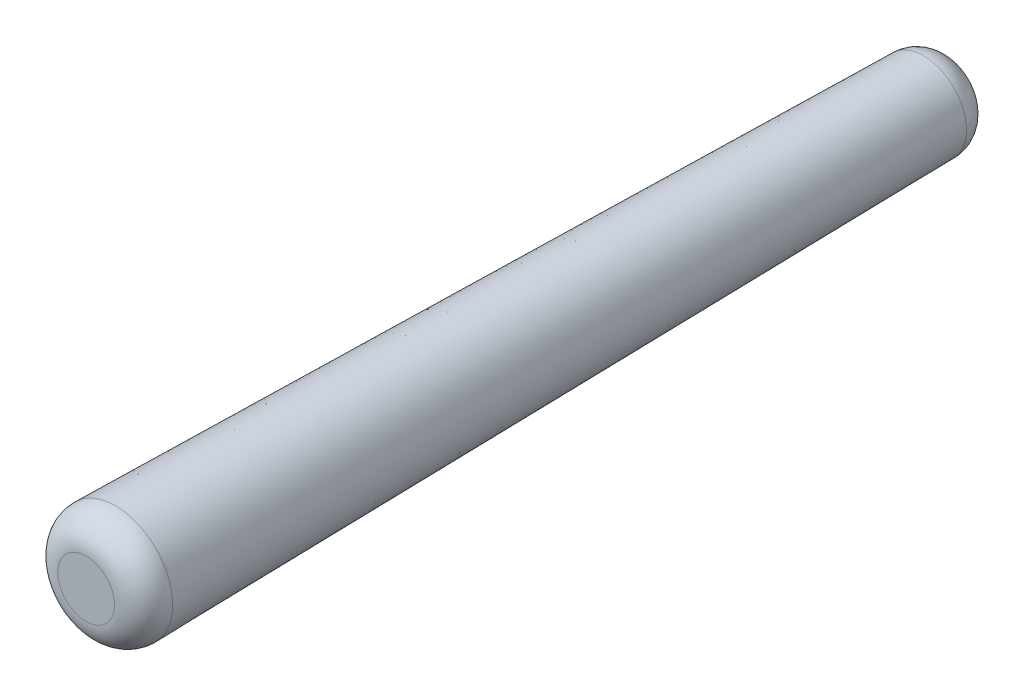
SolidWorks part; units mm, degrees
ref_plane "Front Plane" through (0, 0, 0) normal (0, 0, 1) x (1, 0, 0)
ref_plane "Top Plane" through (0, 0, 0) normal (0, 1, 0) x (1, 0, 0)
ref_plane "Right Plane" through (0, 0, 0) normal (1, 0, 0) x (0, 0, -1)
sketch "Sketch1" plane through (0, 0, 0) normal (0, 0, 1) x (1, 0, 0)
  circle A0 centre (0, 0) radius 2
  dimension "D1" = 4
extrude "Boss-Extrude1" add sketch "Sketch1" against normal blind 30 draft 1
fillet "Fillet1" radius 1 2 edges at (1.4763, 0, -30) (2, 0, 0)
